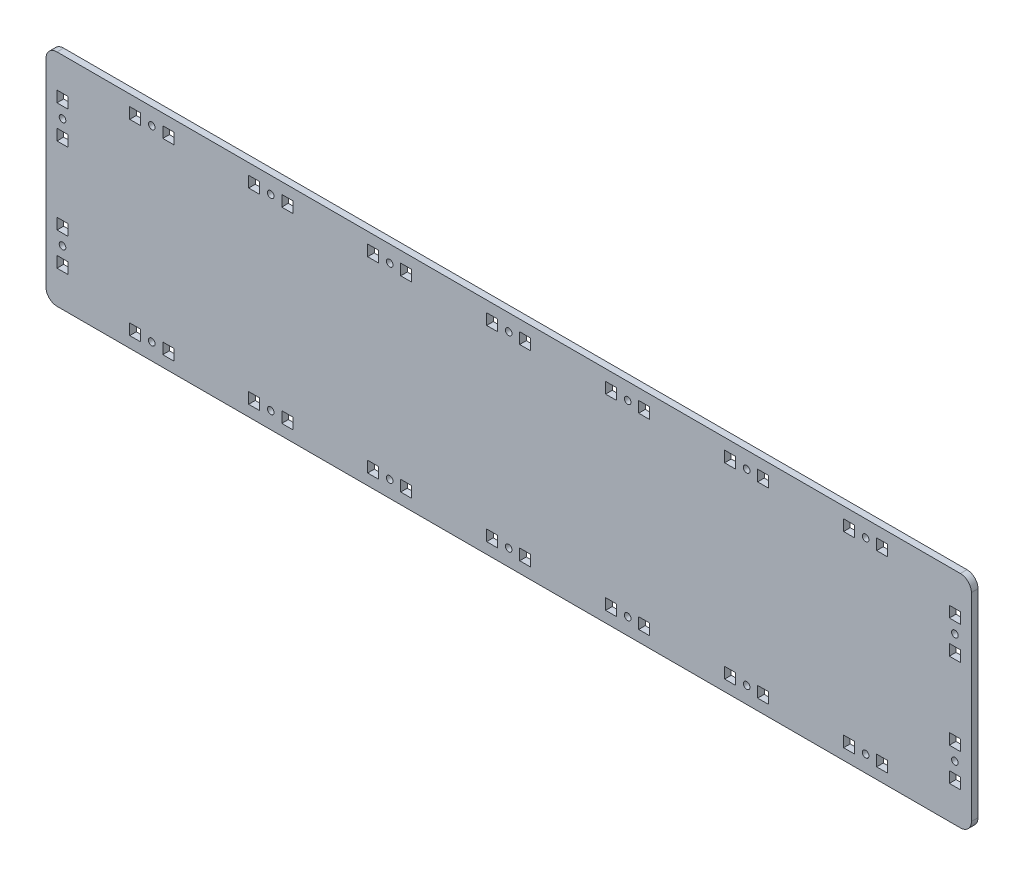
SolidWorks part; units mm, degrees
ref_plane "Front Plane" through (0, 0, 0) normal (0, 0, 1) x (1, 0, 0)
ref_plane "Top Plane" through (0, 0, 0) normal (0, 1, 0) x (1, 0, 0)
ref_plane "Right Plane" through (0, 0, 0) normal (1, 0, 0) x (0, 0, -1)
sketch "Sketch1" plane through (0, 0, 0) normal (0, 0, 1) x (1, 0, 0)
  line L0 (0, 40) -> (0, -40) construction
  line L1 (200, -40) -> (-200, -40) construction
  line L2 (200, -40) -> (200, 40) construction
  line L3 (200, 40) -> (-200, 40) construction
  line L4 (-200, -40) -> (-200, 40) construction
  line L5 (200, -40) -> (-200, 40) construction
  line L6 (200, 40) -> (-200, -40) construction
  line L7 (0, 0) -> (-102.5879, 0) construction
  line L9 (-210, -50) -> (210, -50)
  line L10 (-210, -50) -> (-210, 50)
  line L11 (-210, 50) -> (210, 50)
  line L12 (210, -50) -> (210, 50)
  line L13 (-210, -50) -> (210, 50) construction
  line L14 (-210, 50) -> (210, -50) construction
  point P0 (0, 0)
  line B0 (-5, -40) -> (-10, -40)
  line B1 (-5, -40) -> (-5, -45)
  line B2 (-5, -45) -> (-10, -45)
  line B3 (-10, -40) -> (-10, -45)
  line B4 (5, -40) -> (10, -40)
  line B5 (5, -40) -> (5, -45)
  line B6 (5, -45) -> (10, -45)
  line B7 (10, -40) -> (10, -45)
  circle B8 centre (0, -42.5) radius 1.5
  line B9 (-59, -40) -> (-64, -40)
  line B10 (-59, -40) -> (-59, -45)
  line B11 (-59, -45) -> (-64, -45)
  line B12 (-64, -40) -> (-64, -45)
  line B13 (-49, -40) -> (-44, -40)
  line B14 (-49, -40) -> (-49, -45)
  line B15 (-49, -45) -> (-44, -45)
  line B16 (-44, -40) -> (-44, -45)
  circle B17 centre (-54, -42.5) radius 1.5
  line B18 (-113, -40) -> (-118, -40)
  line B19 (-113, -40) -> (-113, -45)
  line B20 (-113, -45) -> (-118, -45)
  line B21 (-118, -40) -> (-118, -45)
  line B22 (-103, -40) -> (-98, -40)
  line B23 (-103, -40) -> (-103, -45)
  line B24 (-103, -45) -> (-98, -45)
  line B25 (-98, -40) -> (-98, -45)
  circle B26 centre (-108, -42.5) radius 1.5
  line B27 (-167, -40) -> (-172, -40)
  line B28 (-167, -40) -> (-167, -45)
  line B29 (-167, -45) -> (-172, -45)
  line B30 (-172, -40) -> (-172, -45)
  line B31 (-157, -40) -> (-152, -40)
  line B32 (-157, -40) -> (-157, -45)
  line B33 (-157, -45) -> (-152, -45)
  line B34 (-152, -40) -> (-152, -45)
  circle B35 centre (-162, -42.5) radius 1.5
  line B36 (-205, 20) -> (-205, 15)
  line B37 (-205, 20) -> (-200, 20)
  line B38 (-200, 20) -> (-200, 15)
  line B39 (-205, 15) -> (-200, 15)
  line B40 (-205, 30) -> (-205, 35)
  line B41 (-205, 30) -> (-200, 30)
  line B42 (-200, 30) -> (-200, 35)
  line B43 (-205, 35) -> (-200, 35)
  circle B44 centre (-202.5, 25) radius 1.5
  line B45 (59, -40) -> (64, -40)
  line B46 (59, -40) -> (59, -45)
  line B47 (59, -45) -> (64, -45)
  line B48 (64, -40) -> (64, -45)
  line B49 (49, -40) -> (44, -40)
  line B50 (49, -40) -> (49, -45)
  line B51 (49, -45) -> (44, -45)
  line B52 (44, -40) -> (44, -45)
  circle B53 centre (54, -42.5) radius 1.5
  line B54 (113, -40) -> (118, -40)
  line B55 (113, -40) -> (113, -45)
  line B56 (113, -45) -> (118, -45)
  line B57 (118, -40) -> (118, -45)
  line B58 (103, -40) -> (98, -40)
  line B59 (103, -40) -> (103, -45)
  line B60 (103, -45) -> (98, -45)
  line B61 (98, -40) -> (98, -45)
  circle B62 centre (108, -42.5) radius 1.5
  line B63 (167, -40) -> (172, -40)
  line B64 (167, -40) -> (167, -45)
  line B65 (167, -45) -> (172, -45)
  line B66 (172, -40) -> (172, -45)
  line B67 (157, -40) -> (152, -40)
  line B68 (157, -40) -> (157, -45)
  line B69 (157, -45) -> (152, -45)
  line B70 (152, -40) -> (152, -45)
  circle B71 centre (162, -42.5) radius 1.5
  line B72 (-59, 40) -> (-64, 40)
  line B73 (-59, 40) -> (-59, 45)
  line B74 (-59, 45) -> (-64, 45)
  line B75 (-64, 40) -> (-64, 45)
  line B76 (-49, 40) -> (-44, 40)
  line B77 (-49, 40) -> (-49, 45)
  line B78 (-49, 45) -> (-44, 45)
  line B79 (-44, 40) -> (-44, 45)
  circle B80 centre (-54, 42.5) radius 1.5
  line B81 (167, 40) -> (172, 40)
  line B82 (167, 40) -> (167, 45)
  line B83 (167, 45) -> (172, 45)
  line B84 (172, 40) -> (172, 45)
  line B85 (157, 40) -> (152, 40)
  line B86 (157, 40) -> (157, 45)
  line B87 (157, 45) -> (152, 45)
  line B88 (152, 40) -> (152, 45)
  circle B89 centre (162, 42.5) radius 1.5
  line B90 (-113, 40) -> (-118, 40)
  line B91 (-113, 40) -> (-113, 45)
  line B92 (-113, 45) -> (-118, 45)
  line B93 (-118, 40) -> (-118, 45)
  line B94 (-103, 40) -> (-98, 40)
  line B95 (-103, 40) -> (-103, 45)
  line B96 (-103, 45) -> (-98, 45)
  line B97 (-98, 40) -> (-98, 45)
  circle B98 centre (-108, 42.5) radius 1.5
  line B99 (-5, 40) -> (-10, 40)
  line B100 (-5, 40) -> (-5, 45)
  line B101 (-5, 45) -> (-10, 45)
  line B102 (-10, 40) -> (-10, 45)
  line B103 (5, 40) -> (10, 40)
  line B104 (5, 40) -> (5, 45)
  line B105 (5, 45) -> (10, 45)
  line B106 (10, 40) -> (10, 45)
  circle B107 centre (0, 42.5) radius 1.5
  line B108 (-167, 40) -> (-172, 40)
  line B109 (-167, 40) -> (-167, 45)
  line B110 (-167, 45) -> (-172, 45)
  line B111 (-172, 40) -> (-172, 45)
  line B112 (-157, 40) -> (-152, 40)
  line B113 (-157, 40) -> (-157, 45)
  line B114 (-157, 45) -> (-152, 45)
  line B115 (-152, 40) -> (-152, 45)
  circle B116 centre (-162, 42.5) radius 1.5
  line B117 (59, 40) -> (64, 40)
  line B118 (59, 40) -> (59, 45)
  line B119 (59, 45) -> (64, 45)
  line B120 (64, 40) -> (64, 45)
  line B121 (49, 40) -> (44, 40)
  line B122 (49, 40) -> (49, 45)
  line B123 (49, 45) -> (44, 45)
  line B124 (44, 40) -> (44, 45)
  circle B125 centre (54, 42.5) radius 1.5
  line B126 (113, 40) -> (118, 40)
  line B127 (113, 40) -> (113, 45)
  line B128 (113, 45) -> (118, 45)
  line B129 (118, 40) -> (118, 45)
  line B130 (103, 40) -> (98, 40)
  line B131 (103, 40) -> (103, 45)
  line B132 (103, 45) -> (98, 45)
  line B133 (98, 40) -> (98, 45)
  circle B134 centre (108, 42.5) radius 1.5
  line B135 (-205, -20) -> (-205, -15)
  line B136 (-205, -20) -> (-200, -20)
  line B137 (-200, -20) -> (-200, -15)
  line B138 (-205, -15) -> (-200, -15)
  line B139 (-205, -30) -> (-205, -35)
  line B140 (-205, -30) -> (-200, -30)
  line B141 (-200, -30) -> (-200, -35)
  line B142 (-205, -35) -> (-200, -35)
  circle B143 centre (-202.5, -25) radius 1.5
  line B144 (205, 20) -> (205, 15)
  line B145 (205, 20) -> (200, 20)
  line B146 (200, 20) -> (200, 15)
  line B147 (205, 15) -> (200, 15)
  line B148 (205, 30) -> (205, 35)
  line B149 (205, 30) -> (200, 30)
  line B150 (200, 30) -> (200, 35)
  line B151 (205, 35) -> (200, 35)
  circle B152 centre (202.5, 25) radius 1.5
  line B153 (205, -20) -> (205, -15)
  line B154 (205, -20) -> (200, -20)
  line B155 (200, -20) -> (200, -15)
  line B156 (205, -15) -> (200, -15)
  line B157 (205, -30) -> (205, -35)
  line B158 (205, -30) -> (200, -30)
  line B159 (200, -30) -> (200, -35)
  line B160 (205, -35) -> (200, -35)
  circle B161 centre (202.5, -25) radius 1.5
  dimension "D1" = 400
  dimension "D2" = 80
  dimension "D3" = 54
  dimension "D4" = 54
  dimension "D5" = 54
  dimension "D6" = 25
  dimension "D7" = 100
  dimension "D8" = 420
sketch_block_instance "Trou M3 plots 5mm-1"
sketch_block "Trou M3 plots 5mm" parameters "D2"=3, "D1"=5, "D3"=5, "D4"=10
sketch_block_instance "Trou M3 plots 5mm-2"
sketch_block_instance "Trou M3 plots 5mm-3"
sketch_block_instance "Trou M3 plots 5mm-4"
sketch_block_instance "Trou M3 plots 5mm-9"
sketch_block_instance "Trou M3 plots 5mm-13"
sketch_block_instance "Trou M3 plots 5mm-14"
sketch_block_instance "Trou M3 plots 5mm-15"
sketch_block_instance "Trou M3 plots 5mm-16"
sketch_block_instance "Trou M3 plots 5mm-17"
sketch_block_instance "Trou M3 plots 5mm-18"
sketch_block_instance "Trou M3 plots 5mm-19"
sketch_block_instance "Trou M3 plots 5mm-20"
sketch_block_instance "Trou M3 plots 5mm-21"
sketch_block_instance "Trou M3 plots 5mm-22"
sketch_block_instance "Trou M3 plots 5mm-23"
sketch_block_instance "Trou M3 plots 5mm-24"
sketch_block_instance "Trou M3 plots 5mm-25"
extrude "Boss-Extrude1" add sketch "Sketch1" along normal blind 3
fillet "Fillet1" radius 5 4 edges at (-210, -50, 1.5) (-210, 50, 1.5) (210, -50, 1.5) (210, 50, 1.5)
